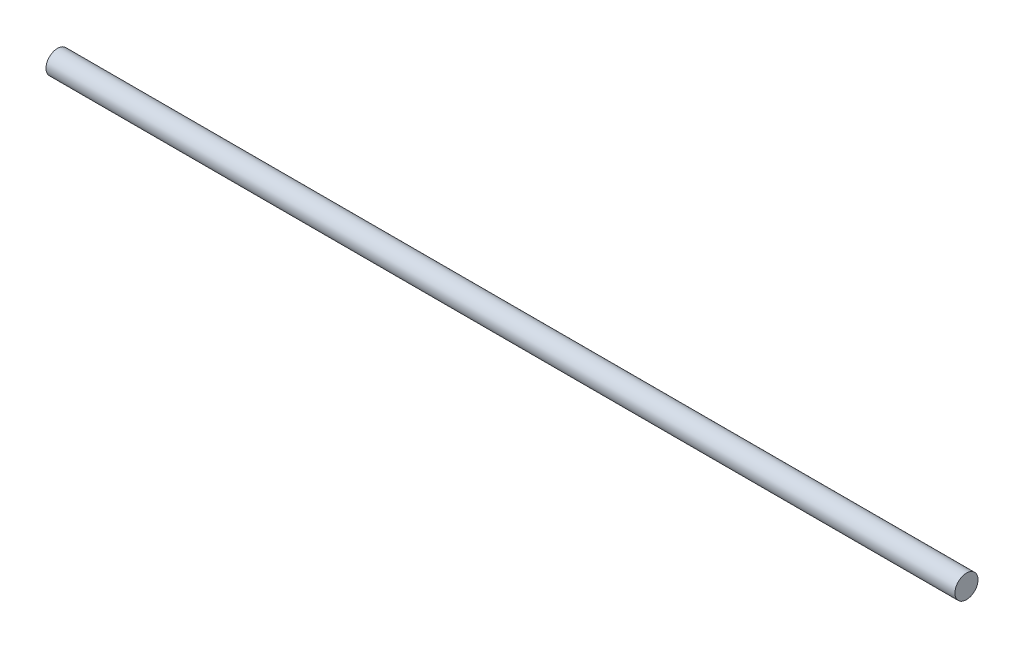
SolidWorks part; units mm, degrees
material "AISI 4130 Steel, annealed at 865C"
ref_plane "Front Plane" through (0, 0, 0) normal (0, 0, 1) x (1, 0, 0)
ref_plane "Top Plane" through (0, 0, 0) normal (0, 1, 0) x (1, 0, 0)
ref_plane "Right Plane" through (0, 0, 0) normal (1, 0, 0) x (0, 0, -1)
sketch "Sketch1" plane through (0, 0, 0) normal (1, 0, 0) x (0, 0, -1)
  circle A0 centre (0, 0) radius 6.35
  dimension "D1" = 12.7
extrude "Boss-Extrude1" add sketch "Sketch1" along normal blind 500
